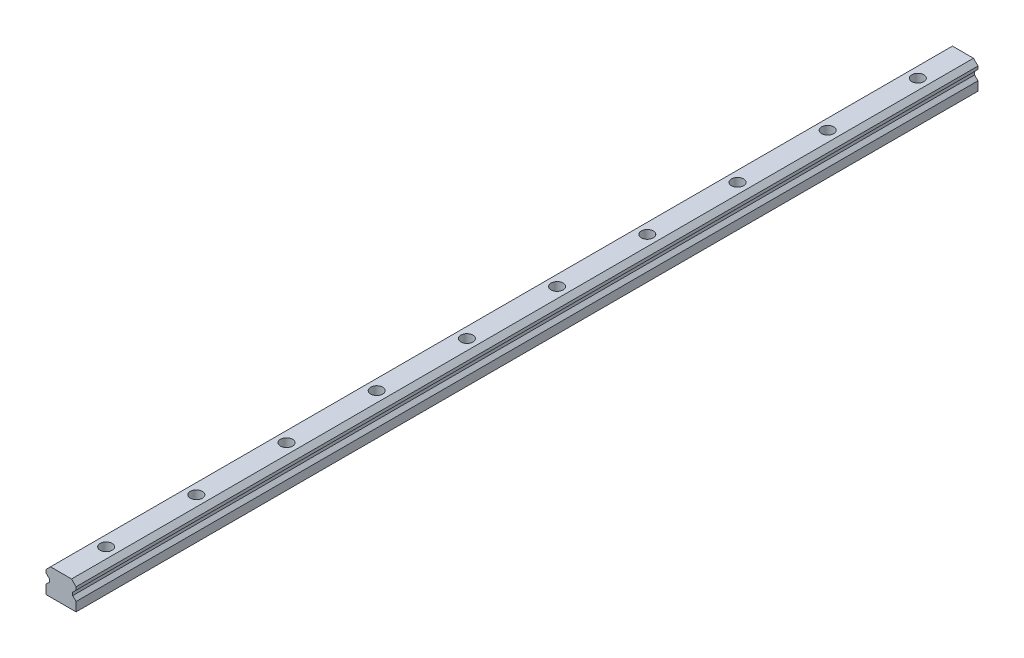
SolidWorks part; units mm, degrees
material "1023 Carbon Steel Sheet (SS)"
ref_plane "Front" through (0, 0, 0) normal (0, 0, 1) x (1, 0, 0)
ref_plane "Top" through (0, 0, 0) normal (0, 1, 0) x (1, 0, 0)
ref_plane "Right" through (0, 0, 0) normal (1, 0, 0) x (0, 0, -1)
sketch "Sketch1" plane through (0, 0, 0) normal (0, 0, 1) x (1, 0, 0)
  line L0 (0, 0) -> (0, 17.5)
  line L1 (7, 17.5) -> (-7, 17.5)
  line L2 (-7, 17.5) -> (-10, 14.5)
  line L3 (-10, 14.5) -> (-10, 12.5)
  line L4 (-10, 12.5) -> (-7.75, 10.25)
  line L5 (-7.75, 10.25) -> (-7.75, 8.25)
  line L6 (-7.75, 8.25) -> (-10, 6)
  line L7 (-10, 6) -> (-10, 0)
  line L8 (-10, 0) -> (10, 0)
  line L9 (10, 6) -> (10, 0)
  line L10 (7.75, 8.25) -> (10, 6)
  line L11 (7.75, 10.25) -> (7.75, 8.25)
  line L12 (10, 12.5) -> (7.75, 10.25)
  line L13 (10, 14.5) -> (10, 12.5)
  line L14 (7, 17.5) -> (10, 14.5)
  dimension "D1" = 17.5
  dimension "D2" = 10
  dimension "D3" = 225
  dimension "D4" = 7
  dimension "D5" = 135
  dimension "D6" = 10
  dimension "D7" = 135
  dimension "D8" = 2
  dimension "D9" = 2
  dimension "D10" = 6
extrude "Boss-Extrude1" add sketch "Sketch1" against normal blind 600 contours L7 L8 L0 L1 L2 L3 L4 L5 L6 | L14 L1 L0 L8 L9 L10 L11 L12 L13
sketch "Sketch2" plane through (0, 17.5, 0) normal (0, 1, 0) x (1, 0, 0)
  line L0 (7, 0) -> (-7, 0) construction
  circle A0 centre (0, 30) radius 4
  circle A1 centre (0, 90) radius 4
  circle A2 centre (0, 150) radius 4
  circle A3 centre (0, 210) radius 4
  circle A4 centre (0, 270) radius 4
  circle A5 centre (0, 330) radius 4
  circle A6 centre (0, 390) radius 4
  circle A7 centre (0, 450) radius 4
  circle A8 centre (0, 510) radius 4
  circle A9 centre (0, 570) radius 4
  dimension "D1" = 8
  dimension "D3" = 30
  dimension "D2" = 10
extrude "Cut-Extrude1" cut sketch "Sketch2" against normal blind 26
